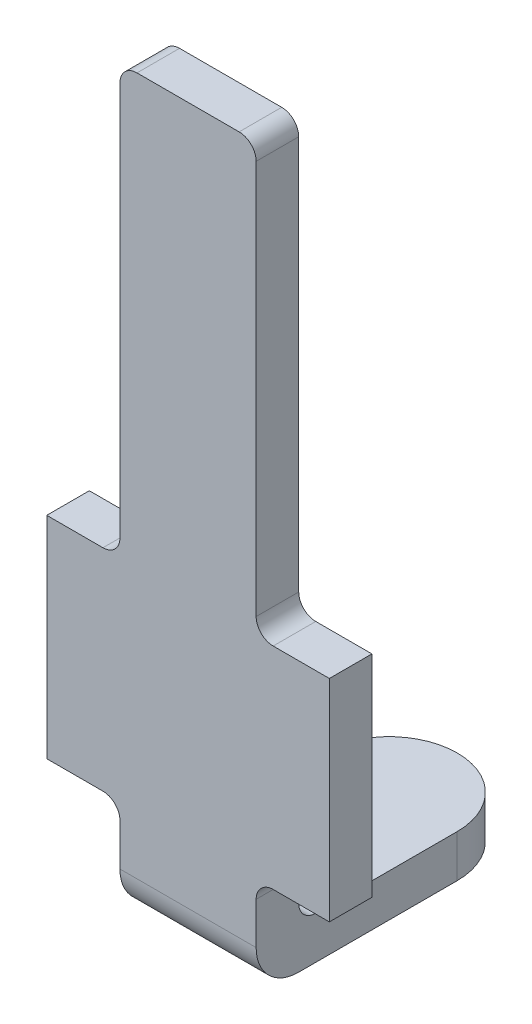
SolidWorks part; units mm, degrees
ref_plane "Front Plane" through (0, 0, 0) normal (0, 0, 1) x (1, 0, 0)
ref_plane "Top Plane" through (0, 0, 0) normal (0, 1, 0) x (1, 0, 0)
ref_plane "Right Plane" through (0, 0, 0) normal (1, 0, 0) x (0, 0, -1)
ref_plane "Plane1" through (0, 3.9, 0) normal (0, 1, 0) x (1, 0, 0)
sketch "Sketch1" plane through (0, 3.9, 0) normal (0, 1, 0) x (1, 0, 0)
  line L0 (-16.91, 0.499) -> (-16.11, 0.499)
  line L1 (-16.11, 0.499) -> (-16.11, 1.68)
  line L2 (-16.91, 1.68) -> (-16.91, 0.499)
  arc A0 (-16.11, 1.68) -> (-16.91, 1.68) centre (-16.51, 1.68) ccw
extrude "Boss-Extrude1" add sketch "Sketch1" against normal blind 4.35
sketch "Sketch2" plane through (-16.11, 0, 0) normal (1, 0, 0) x (0, 0, -1)
  line L0 (0.749, 3.9) -> (0.749, -0.2)
  line L1 (0.749, -0.2) -> (2.5741, -0.2)
  line L2 (2.5741, -0.2) -> (2.5741, 3.9)
  line L3 (2.5741, 3.9) -> (0.749, 3.9)
extrude "Cut-Extrude1" cut sketch "Sketch2" against normal through all
sketch "Sketch3" plane through (-16.11, 0, 0) normal (1, 0, 0) x (0, 0, -1)
  line L0 (0.749, 3.9) -> (0.749, 0.146)
  line L1 (0.749, 0.146) -> (0.499, 0.146)
  line L2 (0.499, 0.146) -> (0.499, 3.9)
  line L3 (0.499, 3.9) -> (0.749, 3.9)
extrude "Boss-Extrude2" add sketch "Sketch3" along normal blind 0.43
sketch "Sketch4" plane through (-16.91, 0, 0) normal (-1, 0, 0) x (0, 0, 1)
  line L0 (-0.499, 3.9) -> (-0.499, 0.146)
  line L1 (-0.499, 0.146) -> (-0.749, 0.146)
  line L2 (-0.749, 0.146) -> (-0.749, 3.9)
  line L3 (-0.749, 3.9) -> (-0.499, 3.9)
extrude "Boss-Extrude3" add sketch "Sketch4" along normal blind 0.43
sketch "Sketch5" plane through (0, 0, -0.749) normal (0, 0, -1) x (-1, 0, 0)
  line L0 (15.68, 1.3844) -> (16.11, 1.3844)
  line L1 (16.11, 1.3844) -> (16.11, 3.9)
  line L2 (16.11, 3.9) -> (15.68, 3.9)
  line L3 (15.68, 3.9) -> (15.68, 1.3844)
extrude "Cut-Extrude2" cut sketch "Sketch5" against normal through all
sketch "Sketch6" plane through (0, 0, -0.749) normal (0, 0, -1) x (-1, 0, 0)
  line L0 (16.91, 1.3844) -> (17.34, 1.3844)
  line L1 (17.34, 1.3844) -> (17.34, 3.9)
  line L2 (17.34, 3.9) -> (16.91, 3.9)
  line L3 (16.91, 3.9) -> (16.91, 1.3844)
extrude "Cut-Extrude3" cut sketch "Sketch6" against normal through all
fillet "Fillet1" radius 0.1 7 edges at (-16.91, 1.3844, -0.624) (-16.91, 3.9, -0.624) (-16.51, -0.2, -0.749) (-16.11, 1.3844, -0.624) (-16.11, 3.9, -0.624) (-16.91, 0.146, -0.624) (-16.11, 0.146, -0.624)
fillet "Fillet2" radius 0.25 1 edges at (-16.51, -0.45, -0.499)
